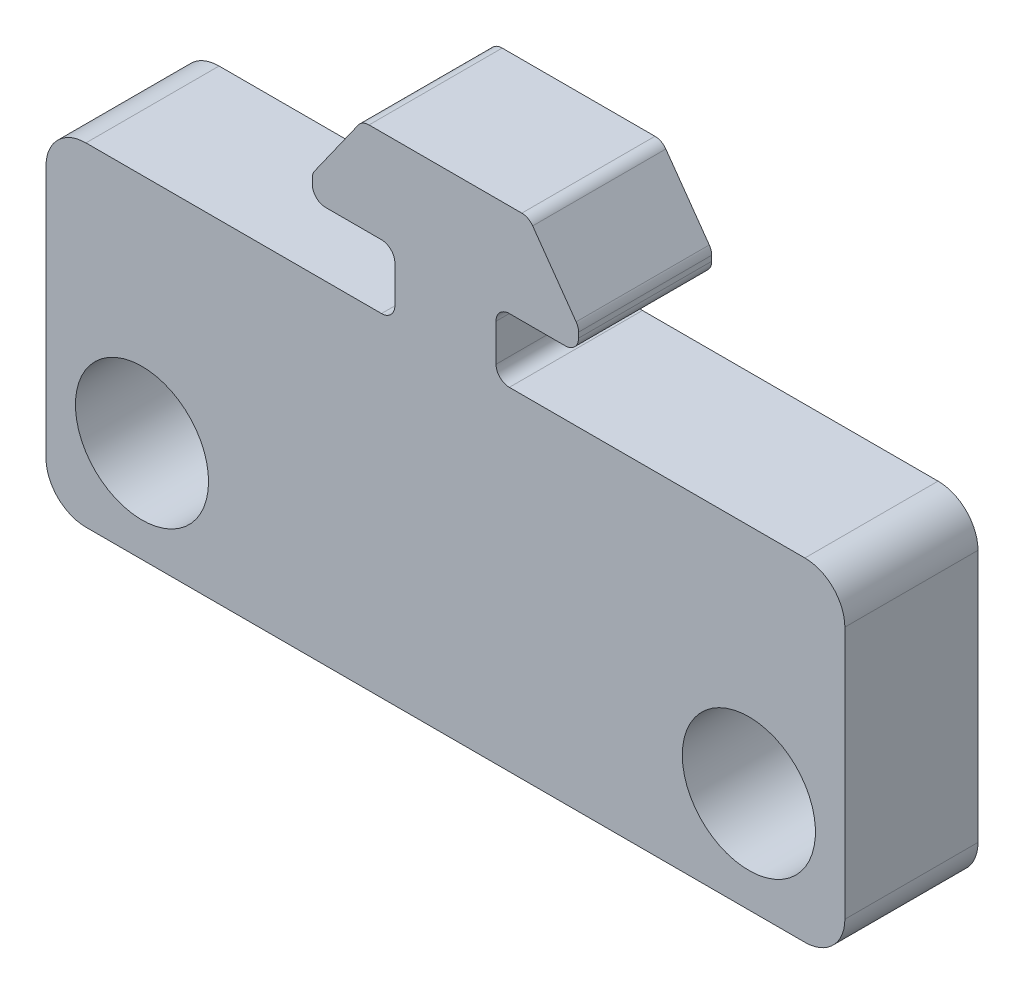
SolidWorks part; units mm, degrees
ref_plane "Front Plane" through (0, 0, 0) normal (0, 0, 1) x (1, 0, 0)
ref_plane "Top Plane" through (0, 0, 0) normal (0, 1, 0) x (1, 0, 0)
ref_plane "Right Plane" through (0, 0, 0) normal (1, 0, 0) x (0, 0, -1)
sketch "Sketch2" plane through (0, 0, 0) normal (0, 0, 1) x (1, 0, 0)
  line L0 (10, 0) -> (-10, 0)
  line L1 (-10, 0) -> (-10, 1.7099)
  line L2 (-10, 1.7099) -> (-6.2548, 7)
  line L3 (-6.2548, 7) -> (6.2548, 7)
  line L4 (0, 7) -> (0, 0)
  line L5 (0, 0) -> (0, 9.2516) construction
  line L6 (10, 1.7099) -> (6.2548, 7)
  line L7 (10, 0) -> (10, 1.7099)
  dimension "D1" = 20
  dimension "D2" = 7
extrude "Boss-Extrude1" add sketch "Sketch2" along normal blind 10 contours L4 L3 L2 L1 L0 | L0 L7 L6 L3 L4
sketch "Sketch4" plane through (0, 0, 0) normal (0, 0, 1) x (1, 0, 0)
  line L0 (-3.8, 0) -> (-3.8, -4.8)
  line L1 (10, 0) -> (-10, 0) construction
  line L2 (-3.8, -4.8) -> (-30, -4.8)
  line L3 (-30, -4.8) -> (-30, -29.8)
  line L4 (-30, -29.8) -> (30, -29.8)
  line L5 (0, 0) -> (0, -29.8) construction
  line L6 (0, -29.8) -> (0, 0)
  line L7 (3.8, 0) -> (-3.8, 0)
  line L8 (0, 0) -> (0, -30.5381) construction
  line L9 (30, -4.8) -> (30, -29.8)
  line L10 (3.8, -4.8) -> (30, -4.8)
  line L11 (3.8, 0) -> (3.8, -4.8)
  line L14 (-30, -22.687) -> (-30, -23.48)
  line L16 (30, -22.687) -> (30, -23.48)
  dimension "D1" = 4.8
  dimension "D2" = 3.8
  dimension "D3" = 25
  dimension "D4" = 60
extrude "Boss-Extrude2" add sketch "Sketch4" along normal blind 10 contours L6 L7 L0 L2 L3 L4 | L11 L7 L6 L4 L9 L10
sketch "Sketch5" plane through (0, 0, 0) normal (0, 0, 1) x (1, 0, 0)
  line L0 (-29.791, -22.2274) -> (26.9734, -22.2274) construction
  line L3 (0, -29.8) -> (0, 7) construction
  line L4 (-30, -29.8) -> (30, -29.8) construction
  line L5 (-6.2548, 7) -> (6.2548, 7) construction
  circle A0 centre (-22.791, -22.2274) radius 5
  circle A1 centre (22.791, -22.2274) radius 5
  dimension "D1" = 7
  dimension "D3" = 7.5726
extrude "Cut-Extrude1" cut sketch "Sketch5" along normal through all
fillet "Fillet1" radius 1 6 edges at (-10, 0, 5) (-10, 1.7099, 5) (-6.2548, 7, 5) (6.2548, 7, 5) (10, 0, 5) (10, 1.7099, 5)
fillet "Fillet2" radius 1 4 edges at (3.8, -4.8, 5) (3.8, 0, 5) (-3.8, -4.8, 5) (-3.8, 0, 5)
fillet "Fillet3" radius 3 4 edges at (-30, -4.8, 5) (-30, -29.8, 5) (30, -4.8, 5) (30, -29.8, 5)
